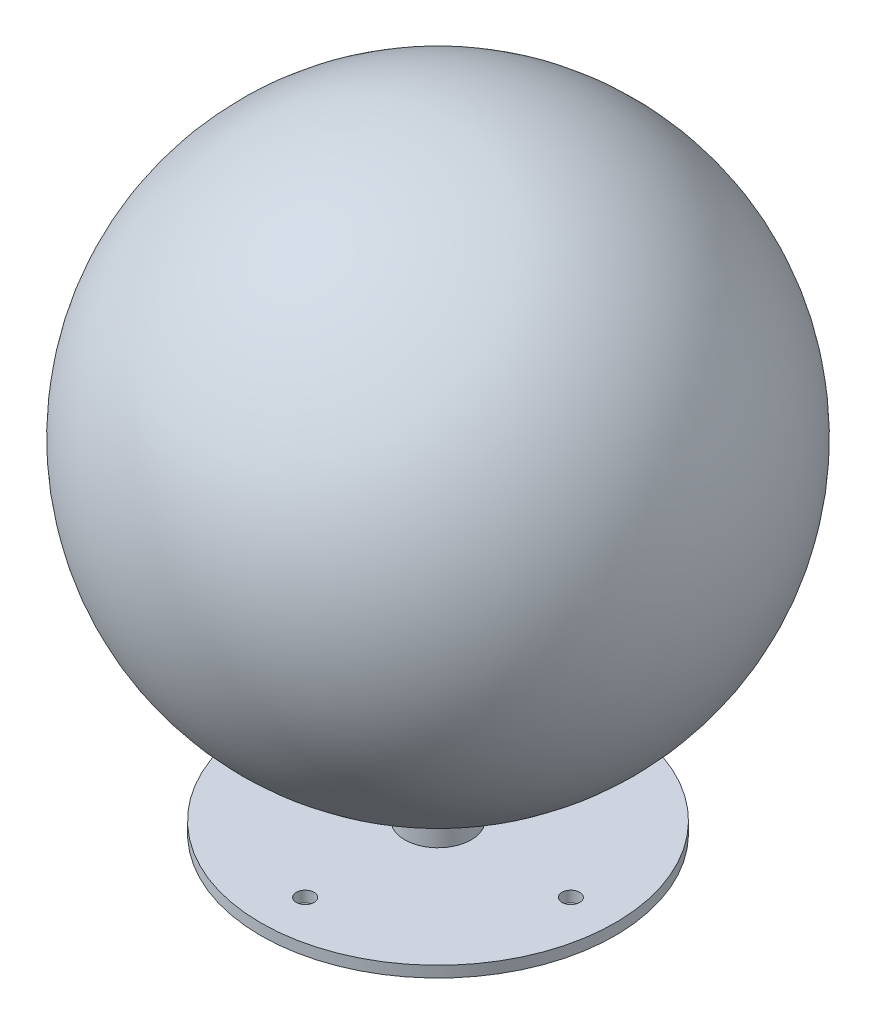
SolidWorks part; units mm, degrees
ref_plane "前视基准面" through (0, 0, 0) normal (0, 0, 1) x (1, 0, 0)
ref_plane "上视基准面" through (0, 0, 0) normal (0, 1, 0) x (1, 0, 0)
ref_plane "右视基准面" through (0, 0, 0) normal (1, 0, 0) x (0, 0, -1)
sketch "草图1" plane through (0, 0, 0) normal (0, 1, 0) x (1, 0, 0)
  circle A0 centre (0, 0) radius 80
extrude "凸台-拉伸1" add sketch "草图1" along normal blind 5
sketch "草图2" plane through (0, 5, 0) normal (0, 1, 0) x (1, 0, 0)
  line L0 (0, 90.6533) -> (0, -90.0879) construction
  line L2 (111.6093, 0) -> (-98.2555, 0) construction
  circle A0 centre (0, 0) radius 60
hole_wizard "大小mm 暗销孔1" positions "3D草图1" profile "草图3" hole size "Ø8.0" standard "ISO"
sketch3d "3D草图1"
  line L0 (0, 5, -90.6533) -> (0, 5, 90.0879) construction
  line L1 (111.6093, 5, 0) -> (-98.2555, 5, 0) construction
  circle A0 centre (0, 5, 0) radius 60 construction
  point P0 (0, 5, -60)
  point P4 (0, 65, 0)
  point P7 (-60, 5, 0)
  point P11 (60, 5, 0)
  point P13 (0, 5, 60)
sketch "草图3" plane through (0, 5, -60) normal (1, 0, 0) x (0, 0, 1)
  line L0 (0, 0) -> (0, 22.4034)
  line L1 (0, 22.4034) -> (4, 20)
  line L2 (4, 20) -> (4, 0)
  line L5 (4, 0) -> (0, 0)
  line L10 (0, 22.4034) -> (-4, 20) construction
  line L11 (0, -6.35) -> (0, 107.95) construction
  dimension "孔直径" = 8
  dimension "孔深度" = 20
  dimension "导头角度" = 118
sketch "草图4" plane through (0, 0, 0) normal (0, 0, 1) x (1, 0, 0)
  line L0 (80, 5) -> (-80, 5) construction
  line L1 (0, 5) -> (15, 5)
  line L2 (0, 5) -> (0, 35)
  line L3 (0, 35) -> (15, 35)
  line L4 (15, 5) -> (15, 35)
  dimension "D1" = 15
  dimension "D2" = 30
revolve "旋转1" add sketch "草图4" angle 360 about L2
sketch "草图5" plane through (0, 0, 0) normal (0, 0, 1) x (1, 0, 0)
  line L0 (0, 35) -> (0, 30)
  line L1 (15, 35) -> (-15, 35) construction
  line L2 (0, 35) -> (0, 280)
  arc A0 (0, 30) -> (0, 280) centre (0, 155) cw
  point P7 (0, 31.6662)
  dimension "D1" = 245
  dimension "D2" = 5
revolve "旋转2" add sketch "草图5" angle 360 about L2
